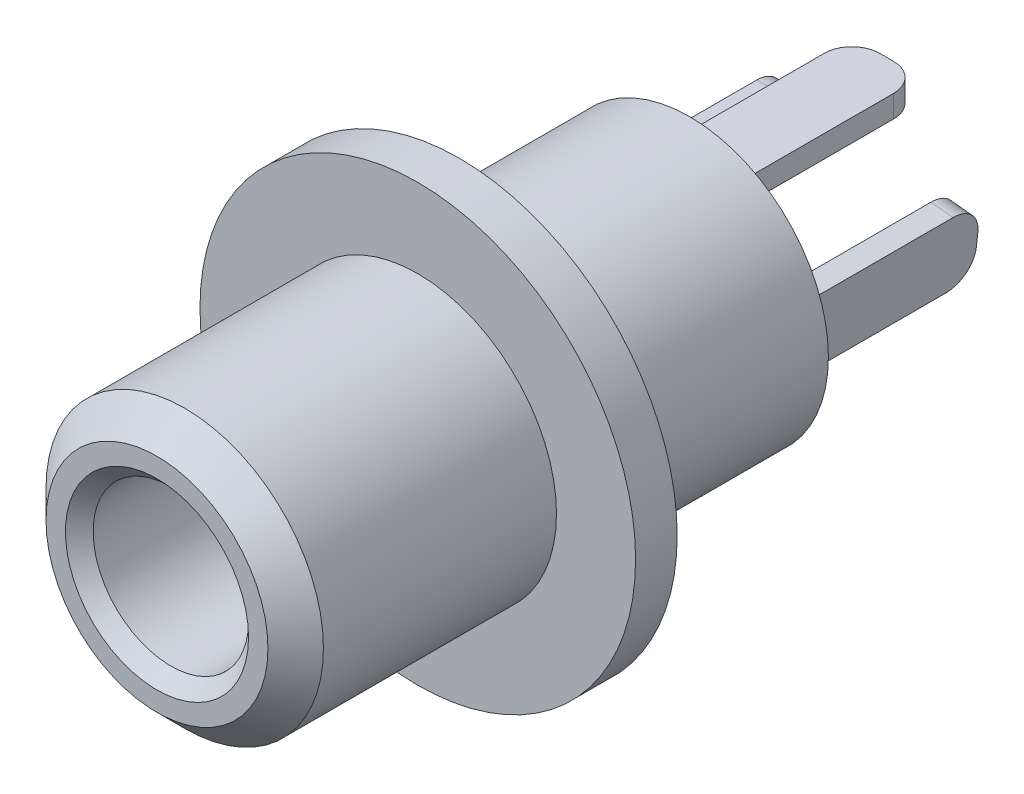
SolidWorks part; units mm, degrees
ref_plane "Front Plane" through (0, 0, 0) normal (0, 0, 1) x (1, 0, 0)
ref_plane "Top Plane" through (0, 0, 0) normal (0, 1, 0) x (1, 0, 0)
ref_plane "Right Plane" through (0, 0, 0) normal (1, 0, 0) x (0, 0, -1)
sketch "Sketch1" plane through (0, 0, 0) normal (0, 0, 1) x (1, 0, 0)
  circle A0 centre (0, 0) radius 5
  dimension "D1" = 10
extrude "Boss-Extrude1" add sketch "Sketch1" along normal blind 9.8
sketch "Sketch2" plane through (0, 0, 9.8) normal (0, 0, 1) x (1, 0, 0)
  circle A0 centre (0, 0) radius 7.85
  dimension "D1" = 15.7
extrude "Boss-Extrude2" add sketch "Sketch2" against normal blind 1.5
sketch "Sketch3" plane through (0, 0, 9.8) normal (0, 0, 1) x (1, 0, 0)
  circle A0 centre (0, 0) radius 5
  dimension "D1" = 10
extrude "Boss-Extrude3" add sketch "Sketch3" along normal blind 9.4
sketch "Sketch4" plane through (0, 0, 0) normal (0, 0, -1) x (-1, 0, 0)
  line L0 (0, 0) -> (0, 6.372) construction
  line L1 (-1.25, 3.3) -> (1.25, 3.3)
  line L2 (-1.25, 3.3) -> (-1.25, 2.5)
  line L3 (-1.25, 2.5) -> (1.25, 2.5)
  line L4 (1.25, 3.3) -> (1.25, 2.5)
  line L5 (3.6855, 1.25) -> (3.6855, -1.25)
  line L6 (3.6855, 1.25) -> (2.8855, 1.25)
  line L7 (2.8855, 1.25) -> (2.8855, -1.25)
  line L8 (3.6855, -1.25) -> (2.8855, -1.25)
  line L13 (-3.1301, -1.9927) -> (-3.3914, 0.4936)
  line L14 (-3.1301, -1.9927) -> (-2.3344, -1.909)
  line L15 (-2.3344, -1.909) -> (-2.5958, 0.5773)
  line L16 (-3.3914, 0.4936) -> (-2.5958, 0.5773)
  point P7 (0, 2.5)
  point P23 (0.1927, -0.1927)
  dimension "D1" = 2.5
  dimension "D2" = 0.8
  dimension "D3" = 2.5
extrude "Boss-Extrude4" add sketch "Sketch4" along normal blind 7.1
fillet "Fillet1" radius 1 6 edges at (-3.2855, -1.25, -7.1) (-3.2855, 1.25, -7.1) (-1.25, 2.9, -7.1) (1.25, 2.9, -7.1) (2.7323, -1.9508, -7.1) (2.9936, 0.5355, -7.1)
sketch "Sketch6" plane through (0, 0, 19.2) normal (0, 0, 1) x (1, 0, 0)
  circle A0 centre (0, 0) radius 2.8
  dimension "D1" = 5.6
extrude "Cut-Extrude1" cut sketch "Sketch6" against normal blind 15
sketch "Sketch7" plane through (0, 0, 4.2) normal (0, 0, 1) x (1, 0, 0)
  circle A0 centre (0, 0) radius 1.25
  dimension "D1" = 2.5
extrude "Boss-Extrude5" add sketch "Sketch7" along normal blind 8
chamfer "Chamfer1" distance 1 angle 45 1 edges at (5, 0, 19.2)
chamfer "Chamfer2" distance 0.5 angle 45 1 edges at (2.8, 0, 19.2)
